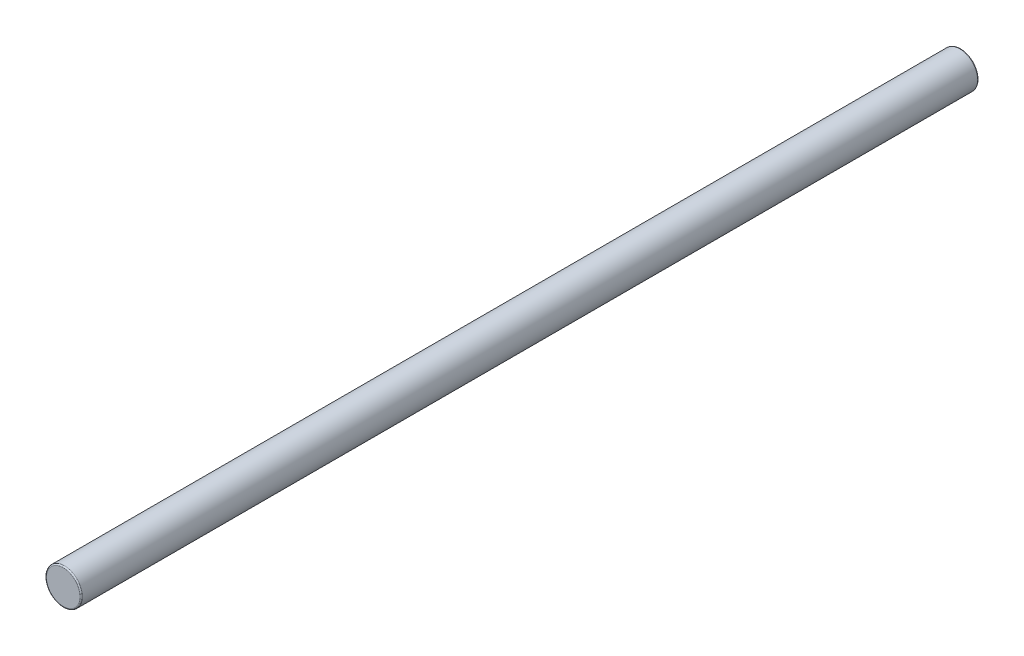
SolidWorks part; units mm, degrees
material "AISI 1020 Steel, Cold Rolled"
ref_plane "Front Plane" through (0, 0, 0) normal (0, 0, 1) x (1, 0, 0)
ref_plane "Top Plane" through (0, 0, 0) normal (0, 1, 0) x (1, 0, 0)
ref_plane "Right Plane" through (0, 0, 0) normal (1, 0, 0) x (0, 0, -1)
sketch "Sketch1" plane through (0, 0, 0) normal (0, 0, 1) x (1, 0, 0)
  circle A0 centre (0, 0) radius 3
  dimension "D1" = 6
extrude "Boss-Extrude1" add sketch "Sketch1" against normal blind 150
fillet "Fillet1" radius 0.2 2 edges at (3, 0, -150) (3, 0, 0)
